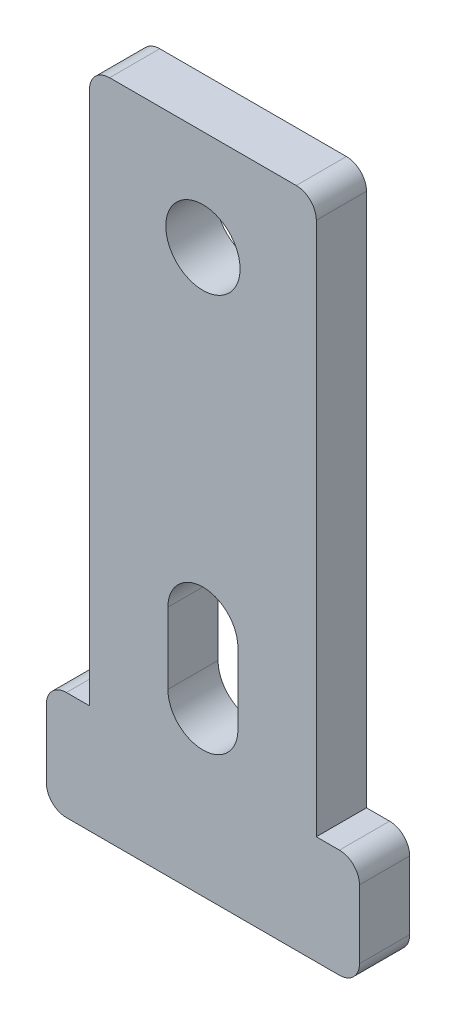
SolidWorks part; units mm, degrees
ref_plane "Alzado" through (0, 0, 0) normal (0, 0, 1) x (1, 0, 0)
ref_plane "Planta" through (0, 0, 0) normal (0, 1, 0) x (1, 0, 0)
ref_plane "Vista lateral" through (0, 0, 0) normal (1, 0, 0) x (0, 0, -1)
sketch "Croquis1" plane through (0, 0, 0) normal (0, 0, 1) x (1, 0, 0)
  line L0 (0, -16.5) -> (-7.8, -16.5) construction
  line L1 (-5.65, -16.5) -> (5.65, -16.5)
  line L2 (-5.65, -11.1) -> (-5.65, 16.5)
  line L3 (-5.65, 16.5) -> (5.65, 16.5)
  line L4 (5.65, -11.1) -> (5.65, 16.5)
  line L5 (-5.65, -16.5) -> (5.65, 16.5) construction
  line L6 (-5.65, 16.5) -> (5.65, -16.5) construction
  line L7 (0, -16.5) -> (7.8, -16.5) construction
  line L8 (0, -16.5) -> (-7.8, -16.5)
  line L9 (-7.8, -16.5) -> (-7.8, -11.1)
  line L10 (-7.8, -11.1) -> (-5.65, -11.1)
  line L11 (7.8, -11.1) -> (7.8, -16.5)
  line L12 (7.8, -16.5) -> (0, -16.5)
  line L13 (5.65, -11.1) -> (7.8, -11.1)
  line L14 (0, 16.5) -> (0, 11.5) construction
  line L15 (0, -16.5) -> (0, -6.5) construction
  line L16 (-1.85, 11.5) -> (-1.85, -13.882) construction
  line L17 (0, -8.436) -> (0, -4.8934) construction
  line L18 (-1.7445, -8.436) -> (-1.7445, -4.8934)
  line L19 (1.7445, -8.436) -> (1.7445, -4.8934)
  circle A0 centre (0, 11.5) radius 1.85
  arc A1 (-1.7445, -8.436) -> (1.7445, -8.436) centre (0, -8.436) ccw
  arc A2 (1.7445, -4.8934) -> (-1.7445, -4.8934) centre (0, -4.8934) ccw
  point P0 (0, 0)
  point P21 (0, -6.6647)
  dimension "D3" = 3.7
  dimension "D1" = 11.3
  dimension "D2" = 33
extrude "Saliente-Extruir1" add sketch "Croquis1" along normal blind 2.5 contours L13 L4 L3 L2 L10 L9 L8 L1 L12 L11 A2 L19 A1 L18 A0
fillet "Redondeo1" radius 1 6 edges at (-7.8, -16.5, 1.25) (-7.8, -11.1, 1.25) (7.8, -16.5, 1.25) (7.8, -11.1, 1.25) (5.65, 16.5, 1.25) (-5.65, 16.5, 1.25)
